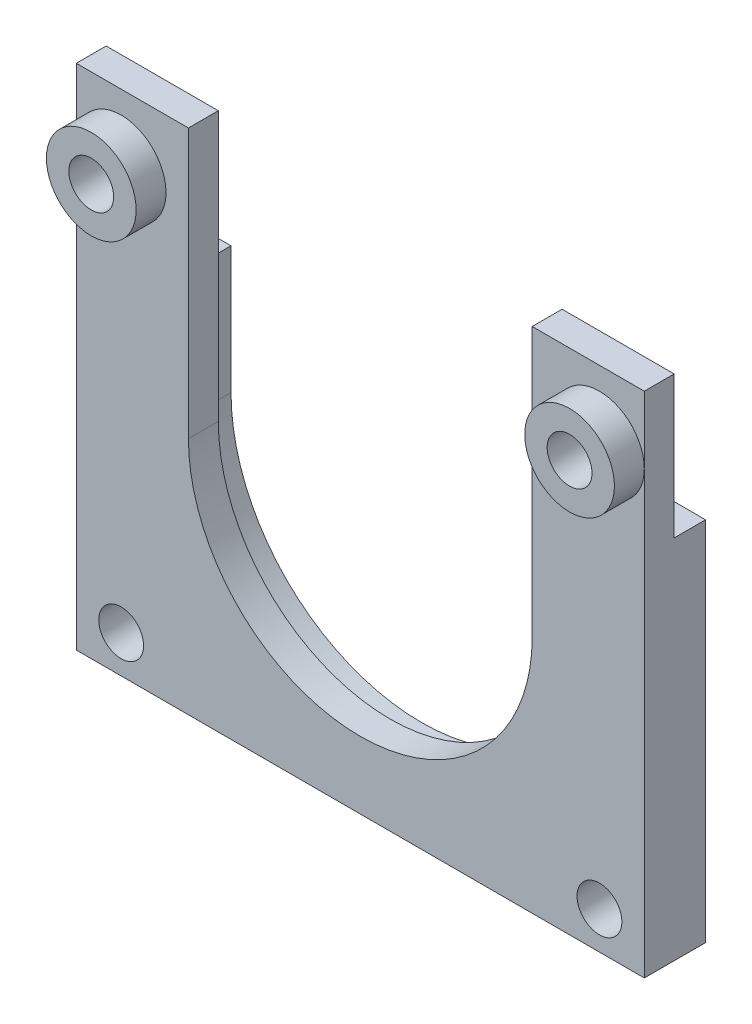
SolidWorks part; units mm, degrees
material "ABS"
ref_plane "前视基准面" through (0, 0, 0) normal (0, 0, 1) x (1, 0, 0)
ref_plane "上视基准面" through (0, 0, 0) normal (0, 1, 0) x (1, 0, 0)
ref_plane "右视基准面" through (0, 0, 0) normal (1, 0, 0) x (0, 0, -1)
sketch "草图1" plane through (0, 0, 0) normal (0, 0, 1) x (1, 0, 0)
  line L0 (-12.75, 0) -> (-12.75, 16)
  line L1 (19, 16) -> (12.75, 16)
  line L2 (19, 16) -> (19, -16)
  line L3 (19, -16) -> (-19, -16)
  line L4 (-19, 16) -> (-19, -16)
  line L5 (0, -16) -> (0, 19) construction
  line L6 (19, 0) -> (-19, 0) construction
  line L7 (12.75, 0) -> (12.75, 16)
  line L8 (-12.75, 16) -> (-19, 16)
  arc A0 (-12.75, 0) -> (12.75, 0) centre (0, 0) ccw
  circle A1 centre (-16, 13.5) radius 1.5
  circle A2 centre (16, 13.5) radius 1.5
  circle A3 centre (16, -13.5) radius 1.5
  circle A4 centre (-16, -13.5) radius 1.5
  point P0 (0, 0)
  dimension "D3" = 25.5
  dimension "D5" = 3
  dimension "D6" = 3
  dimension "D1" = 38
  dimension "D2" = 32
  dimension "D4" = 32
  dimension "D7" = 16
  dimension "D8" = 13.5
extrude "凸台-拉伸1" add sketch "草图1" along normal blind 4.1
sketch "草图2" plane through (0, 0, 4.1) normal (0, 0, 1) x (1, 0, 0)
  line L0 (-12.75, 0) -> (-12.75, 16)
  line L1 (-12.75, 16) -> (-11.5, 16)
  line L2 (-11.5, 16) -> (-11.5, 0)
  line L3 (11.5, 0) -> (11.5, 16)
  line L4 (11.5, 16) -> (12.75, 16)
  line L5 (12.75, 16) -> (12.75, 0)
  arc A0 (-12.75, 0) -> (12.75, 0) centre (0, 0) ccw
  arc A1 (-11.5, 0) -> (11.5, 0) centre (0, 0) ccw
  dimension "D1" = 11.5
extrude "凸台-拉伸2" add sketch "草图2" against normal blind 2
sketch "草图3" plane through (0, 0, 0) normal (0, 0, -1) x (-1, 0, 0)
  line L1 (55.2048, 18.5) -> (-23.2048, 18.5)
  line L2 (55.2048, 18.5) -> (55.2048, 8.5)
  line L3 (55.2048, 8.5) -> (-23.2048, 8.5)
  line L4 (-23.2048, 18.5) -> (-23.2048, 8.5)
  line L5 (16, 8.5) -> (16, 18.5) construction
  line L6 (55.2048, 13.5) -> (-23.2048, 13.5) construction
  point P0 (16, 13.5)
  dimension "D1" = 10
extrude "切除-拉伸1" cut sketch "草图3" against normal up to surface (2.1 mm away) up to face at (0, 4.9688, 2.1)
sketch "草图4" plane through (0, 0, 4.1) normal (0, 0, 1) x (1, 0, 0)
  line L0 (0, 22.5822) -> (0, -21.2062) construction
  line L1 (-19, 16) -> (-11.5, 16)
  line L2 (-19, 16) -> (-19, 18)
  line L3 (-19, 18) -> (-11.5, 18)
  line L4 (-11.5, 16) -> (-11.5, 18)
  line L5 (11.5, 16) -> (11.5, 18)
  line L6 (19, 18) -> (11.5, 18)
  line L7 (19, 16) -> (19, 18)
  line L8 (19, 16) -> (11.5, 16)
  line L9 (-11.5, 0) -> (-11.5, 16) construction
  dimension "D1" = 2
extrude "凸台-拉伸3" add sketch "草图4" against normal up to surface (2 mm away) up to face at (0, 6.1458, 2.1)
sketch "草图5" plane through (0, 0, 4.1) normal (0, 0, 1) x (1, 0, 0)
  circle A0 centre (-16, 13.5) radius 3
  circle A1 centre (16, 13.5) radius 3
  circle A2 centre (16, 13.5) radius 1.5 construction
  circle A3 centre (-16, 13.5) radius 1.5 construction
  circle A4 centre (16, 13.5) radius 1.5
  circle A5 centre (-16, 13.5) radius 1.5
  dimension "D1" = 6
  dimension "D2" = 6
extrude "凸台-拉伸4" add sketch "草图5" along normal blind 2
